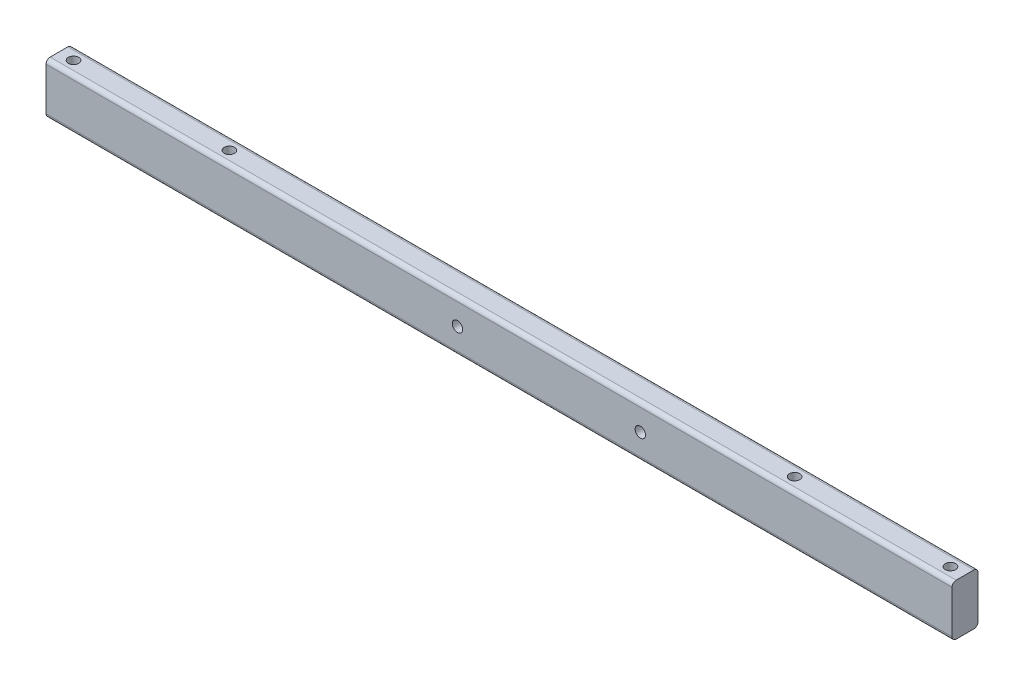
SolidWorks part; units mm, degrees
material "1060 Alloy"
ref_plane "Front Plane" through (0, 0, 0) normal (0, 0, 1) x (1, 0, 0)
ref_plane "Top Plane" through (0, 0, 0) normal (0, 1, 0) x (1, 0, 0)
ref_plane "Right Plane" through (0, 0, 0) normal (1, 0, 0) x (0, 0, -1)
sketch "Sketch1" plane through (0, 0, 0) normal (0, 0, 1) x (1, 0, 0)
  line L0 (-218, 6.15) -> (218, 6.15) construction
  line L1 (0, 0) -> (218, 0)
  line L2 (0, 0) -> (0, 12.3)
  line L3 (0, 12.3) -> (218, 12.3)
  line L4 (218, 0) -> (218, 12.3)
  circle A0 centre (143, 6.15) radius 1.25
  circle A1 centre (99, 6.15) radius 1.25
  point P8 (0, 6.15)
  dimension "D3" = 75
  dimension "D4" = 44
  dimension "D5" = 2.5
  dimension "D6" = 2.5
  dimension "D1" = 218
  dimension "D2" = 12.3
extrude "Boss-Extrude1" add sketch "Sketch1" along normal blind 6.25
sketch "Sketch2" plane through (0, 12.3, 0) normal (0, 1, 0) x (1, 0, 0)
  line L0 (109, 6.25) -> (109, -6.25) construction
  line L2 (218, -6.25) -> (0, -6.25) construction
  line L3 (327, -3.125) -> (109, -3.125) construction
  line L5 (218, -6.25) -> (218, 0) construction
  circle A0 centre (214.5, -3.125) radius 1.25
  circle A1 centre (177, -3.125) radius 1.25
  circle A2 centre (3.5, -3.125) radius 1.25
  circle A3 centre (41, -3.125) radius 1.25
  point P3 (109, 0)
  point P8 (218, -3.125)
  dimension "D1" = 3.5
  dimension "D2" = 2.5
  dimension "D3" = 37.5
  dimension "D4" = 2.5
extrude "Cut-Extrude1" cut sketch "Sketch2" against normal blind 8
fillet "Fillet1" radius 1 4 edges at (109, 12.3, 0) (109, 0, 0) (109, 0, 6.25) (109, 12.3, 6.25)
move or copy body "Body-Move/Copy1" bodies to move or copy 103
